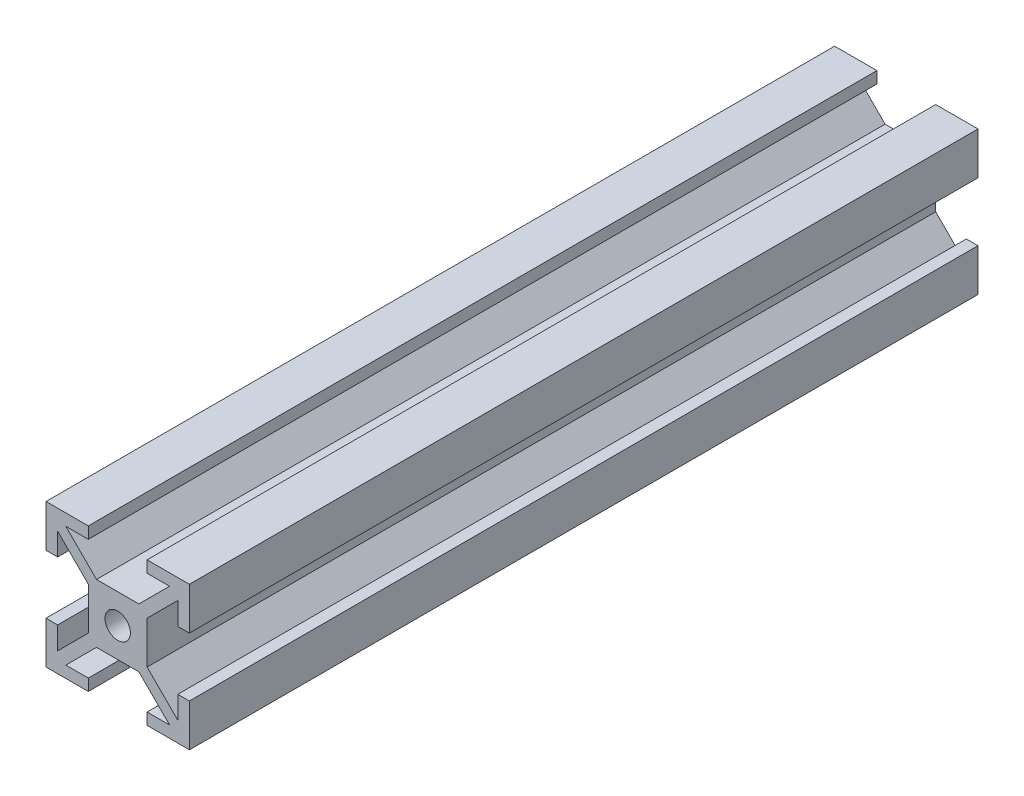
SolidWorks part; units mm, degrees
ref_plane "Front Plane" through (0, 0, 0) normal (0, 0, 1) x (1, 0, 0)
ref_plane "Top Plane" through (0, 0, 0) normal (0, 1, 0) x (1, 0, 0)
ref_plane "Right Plane" through (0, 0, 0) normal (1, 0, 0) x (0, 0, -1)
sketch "Sketch1" plane through (0, 0, 0) normal (0, 0, 1) x (1, 0, 0)
  line L0 (-8.38, 4.1) -> (-10, 4.1)
  line L1 (-2.9545, 4.1) -> (2.9545, 4.1)
  line L2 (-4.1, 2.9545) -> (-4.1, -2.9545)
  line L3 (-2.9545, -4.1) -> (2.9545, -4.1)
  line L4 (4.1, 2.9545) -> (4.1, -2.9545)
  line L5 (-4.1, 4.1) -> (4.1, -4.1) construction
  line L6 (-4.1, -4.1) -> (4.1, 4.1) construction
  line L7 (-10, 10) -> (-4.1, 10)
  line L8 (-10, 10) -> (-10, 4.1)
  line L9 (-10, -10) -> (-4.1, -10)
  line L10 (10, 10) -> (10, 4.1)
  line L11 (-10, 10) -> (10, -10) construction
  line L12 (-10, -10) -> (10, 10) construction
  line L13 (-7.2345, 8.38) -> (-4.1, 8.38)
  line L14 (-8.38, 7.2345) -> (-8.38, 4.1)
  line L15 (-7.2345, -8.38) -> (-4.1, -8.38)
  line L16 (8.38, 7.2345) -> (8.38, 4.1)
  line L17 (-8.38, 8.38) -> (8.38, -8.38) construction
  line L18 (-8.38, -8.38) -> (8.38, 8.38) construction
  line L19 (-4.1, 8.38) -> (-4.1, 10)
  line L20 (4.1, 10) -> (4.1, 8.38)
  line L21 (8.38, 4.1) -> (10, 4.1)
  line L22 (-8.38, -4.1) -> (-10, -4.1)
  line L23 (-4.1, -8.38) -> (-4.1, -10)
  line L24 (8.38, -4.1) -> (10, -4.1)
  line L25 (4.1, -8.38) -> (4.1, -10)
  line L26 (-5.464, 5.464) -> (-4.8912, 6.0368) construction
  line L27 (-4.1, 2.9545) -> (-8.38, 7.2345)
  line L28 (-2.9545, 4.1) -> (-7.2345, 8.38)
  line L29 (0, 11.3108) -> (0, -17.1823) construction
  line L30 (-16.7028, 0) -> (14.4032, 0) construction
  line L31 (-2.9545, -4.1) -> (-7.2345, -8.38)
  line L32 (-4.1, -2.9545) -> (-8.38, -7.2345)
  line L33 (2.9545, -4.1) -> (7.2345, -8.38)
  line L34 (4.1, -2.9545) -> (8.38, -7.2345)
  line L35 (4.1, 2.9545) -> (8.38, 7.2345)
  line L36 (2.9545, 4.1) -> (7.2345, 8.38)
  line L37 (4.1, 8.38) -> (7.2345, 8.38)
  line L38 (4.1, 10) -> (10, 10)
  line L39 (-8.38, -4.1) -> (-8.38, -7.2345)
  line L40 (-10, -4.1) -> (-10, -10)
  line L41 (8.38, -4.1) -> (8.38, -7.2345)
  line L42 (10, -4.1) -> (10, -10)
  line L43 (4.1, -8.38) -> (7.2345, -8.38)
  line L44 (4.1, -10) -> (10, -10)
  circle A0 centre (0, 0) radius 1.77
  point P0 (0, 0)
  point P6 (0, 0)
  dimension "D5" = 3.54
  dimension "D1" = 8.2
  dimension "D2" = 20
  dimension "D3" = 8.2
  dimension "D4" = 20
  dimension "D6" = 16.76
  dimension "D7" = 16.76
  dimension "D8" = 0.81
  dimension "D9" = 135
  dimension "D10" = 7.7696
  dimension "D11" = 5.0536
extrude "Boss-Extrude1" add sketch "Sketch1" along normal blind 110
